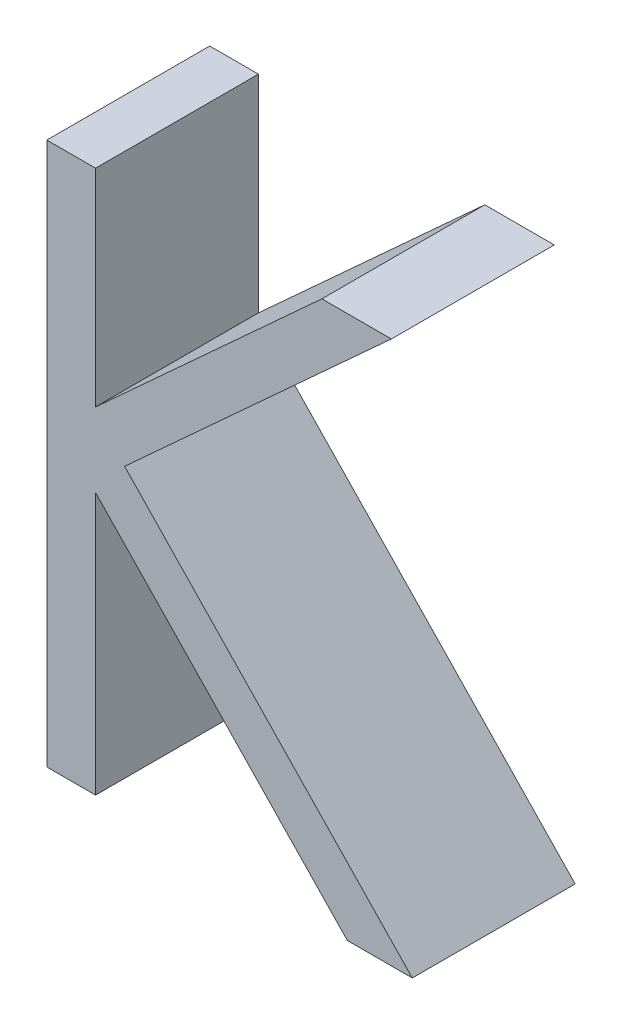
SolidWorks part; units mm, degrees
ref_plane "Plan de face" through (0, 0, 0) normal (0, 0, 1) x (1, 0, 0)
ref_plane "Plan de dessus" through (0, 0, 0) normal (0, 1, 0) x (1, 0, 0)
ref_plane "Plan de droite" through (0, 0, 0) normal (1, 0, 0) x (0, 0, -1)
sketch "Esquisse1" plane through (0, 0, 0) normal (0, 0, 1) x (1, 0, 0)
  text T0 "K" font "Century Gothic" height 5
extrude "Boss.-Extru.1" add sketch "Esquisse1" along normal blind 1.5
